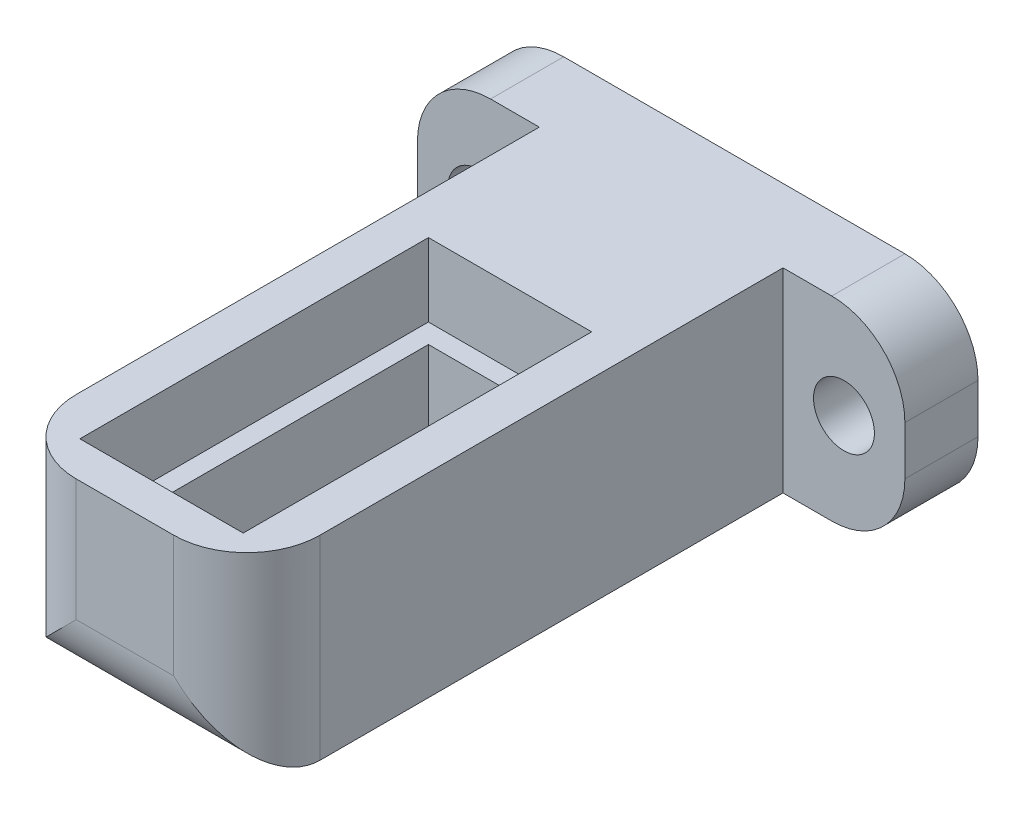
SolidWorks part; units mm, degrees
ref_plane "Plano frontal" through (0, 0, 0) normal (0, 0, 1) x (1, 0, 0)
ref_plane "Plano superior" through (0, 0, 0) normal (0, 1, 0) x (1, 0, 0)
ref_plane "Plano direito" through (0, 0, 0) normal (1, 0, 0) x (0, 0, -1)
sketch "Esboço1" plane through (0, 0, 0) normal (0, 1, 0) x (1, 0, 0)
  line L1 (-5, -12.5) -> (5, -12.5)
  line L2 (-5, -12.5) -> (-5, 12.5)
  line L3 (-5, 12.5) -> (5, 12.5)
  line L4 (5, -12.5) -> (5, 12.5)
  line L5 (-5, -12.5) -> (5, 12.5) construction
  line L6 (-5, 12.5) -> (5, -12.5) construction
  point P0 (0, 0)
  dimension "D1" = 10
  dimension "D2" = 25
extrude "Ressalto-extrusão1" add sketch "Esboço1" along normal blind 8
sketch "Esboço2" plane through (0, 8, 0) normal (0, 1, 0) x (1, 0, 0)
  line L0 (-5, -12.5) -> (5, -12.5) construction
  line L1 (-3.35, 3.3) -> (3.35, 3.3)
  line L2 (-3.35, 3.3) -> (-3.35, -11)
  line L3 (-3.35, -11) -> (3.35, -11)
  line L4 (3.35, 3.3) -> (3.35, -11)
  point P4 (0, -11)
  point P7 (0, -12.5)
  dimension "D1" = 0
  dimension "D2" = 6.7
  dimension "D3" = 14.3
  dimension "D4" = 1.5
extrude "Corte-extrusão1" cut sketch "Esboço2" against normal blind 3
sketch "Esboço3" plane through (0, 0, -12.5) normal (0, 0, -1) x (-1, 0, 0)
  line L1 (-5, 8) -> (-10, 8)
  line L2 (-5, 8) -> (-5, 0)
  line L3 (-5, 0) -> (-10, 0)
  line L4 (-10, 8) -> (-10, 0)
  dimension "D1" = 5
extrude "Ressalto-extrusão2" add sketch "Esboço3" against normal blind 3
sketch "Esboço5" plane through (0, 0, -9.5) normal (0, 0, 1) x (1, 0, 0)
  line L0 (5, 8) -> (10, 8) construction
  circle A0 centre (7.5, 4) radius 1.25
  point P4 (7.5, 8)
  dimension "D1" = 2.5
  dimension "D2" = 0
extrude "Corte-extrusão2" cut sketch "Esboço5" against normal through all
fillet "Filete1" radius 3 2 edges at (10, 0, -11) (10, 8, -11)
mirror "Espelhar3" about plane through (0, 0, 0) normal (1, 0, 0) of "Ressalto-extrusão2", "Filete1", "Corte-extrusão2"
sketch "Esboço6" plane through (0, 5, 0) normal (0, 1, 0) x (1, 0, 0)
  line L8 (-2.55, 2.5) -> (-2.55, -10.2)
  line L9 (-2.55, -10.2) -> (2.55, -10.2)
  line L10 (2.55, -10.2) -> (2.55, 2.5)
  line L11 (2.55, 2.5) -> (-2.55, 2.5)
  line L12 (-2.55, 2.5) -> (-2.55, -10.2)
  line L13 (-2.55, -10.2) -> (2.55, -10.2)
  line L14 (2.55, -10.2) -> (2.55, 2.5)
  line L15 (2.55, 2.5) -> (-2.55, 2.5)
  dimension "D1" = 0.8
extrude "Corte-extrusão3" cut sketch "Esboço6" against normal blind 3
sketch "Esboço7" plane through (0, 2, 0) normal (0, 1, 0) x (1, 0, 0)
  line L0 (2.55, 2.5) -> (-2.55, 2.5) construction
  circle A0 centre (0, -0.5) radius 2
  dimension "D1" = 4
  dimension "D2" = 3
extrude "Corte-extrusão4" cut sketch "Esboço7" against normal through all
fillet "Filete2" radius 3 3 edges at (5, 4, 12.5) (-5, 4, 12.5) (0, 0, 12.5)
